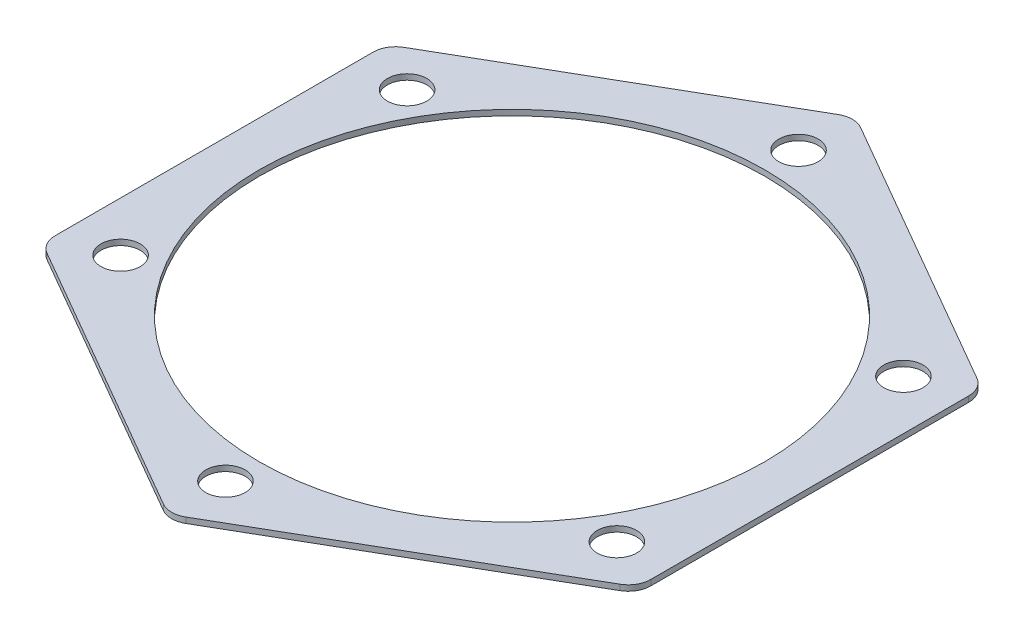
SolidWorks part; units mm, degrees
ref_plane "Front Plane" through (0, 0, 0) normal (0, 0, 1) x (1, 0, 0)
ref_plane "Top Plane" through (0, 0, 0) normal (0, 1, 0) x (1, 0, 0)
ref_plane "Right Plane" through (0, 0, 0) normal (1, 0, 0) x (0, 0, -1)
sketch "Sketch1" plane through (0, 0, 0) normal (0, 1, 0) x (1, 0, 0)
  line L1 (2, -60.0444) -> (51, -31.7543)
  line L2 (53, -28.2902) -> (53, 28.2902)
  line L3 (51, 31.7543) -> (2, 60.0444)
  line L4 (-2, 60.0444) -> (-51, 31.7543)
  line L5 (-53, 28.2902) -> (-53, -28.2902)
  line L6 (-51, -31.7543) -> (-2, -60.0444)
  circle A0 centre (0, 0) radius 53 construction
  arc A1 (-53, 28.2902) -> (-51, 31.7543) centre (-49, 28.2902) cw
  arc A2 (-53, -28.2902) -> (-51, -31.7543) centre (-49, -28.2902) ccw
  arc A3 (2, -60.0444) -> (-2, -60.0444) centre (0, -56.5803) cw
  arc A4 (51, -31.7543) -> (53, -28.2902) centre (49, -28.2902) ccw
  arc A5 (53, 28.2902) -> (51, 31.7543) centre (49, 28.2902) ccw
  arc A6 (2, 60.0444) -> (-2, 60.0444) centre (0, 56.5803) ccw
  point P21 (0, 61.1991)
  dimension "D2" = 4
  dimension "D1" = 106
extrude "Boss-Extrude1" add sketch "Sketch1" along normal blind 1
sketch "Sketch2" plane through (0, 1, 0) normal (0, 1, 0) x (1, 0, 0)
  circle A0 centre (0, 0) radius 51 construction
  circle A1 centre (0, 51) radius 3.5
  circle A2 centre (44.1673, 25.5) radius 3.5
  circle A3 centre (44.1673, -25.5) radius 3.5
  circle A4 centre (0, -51) radius 3.5
  circle A5 centre (-44.1673, -25.5) radius 3.5
  circle A6 centre (-44.1673, 25.5) radius 3.5
  point P18 (0, 0)
  dimension "D1" = 102
  dimension "D2" = 7
  dimension "D3" = 6
extrude "Cut-Extrude1" cut sketch "Sketch2" against normal through all
sketch "Sketch3" plane through (0, 0, 0) normal (0, -1, 0) x (1, 0, 0)
  circle A0 centre (0, 0) radius 45
  dimension "D1" = 90
extrude "Cut-Extrude2" cut sketch "Sketch3" against normal through all
